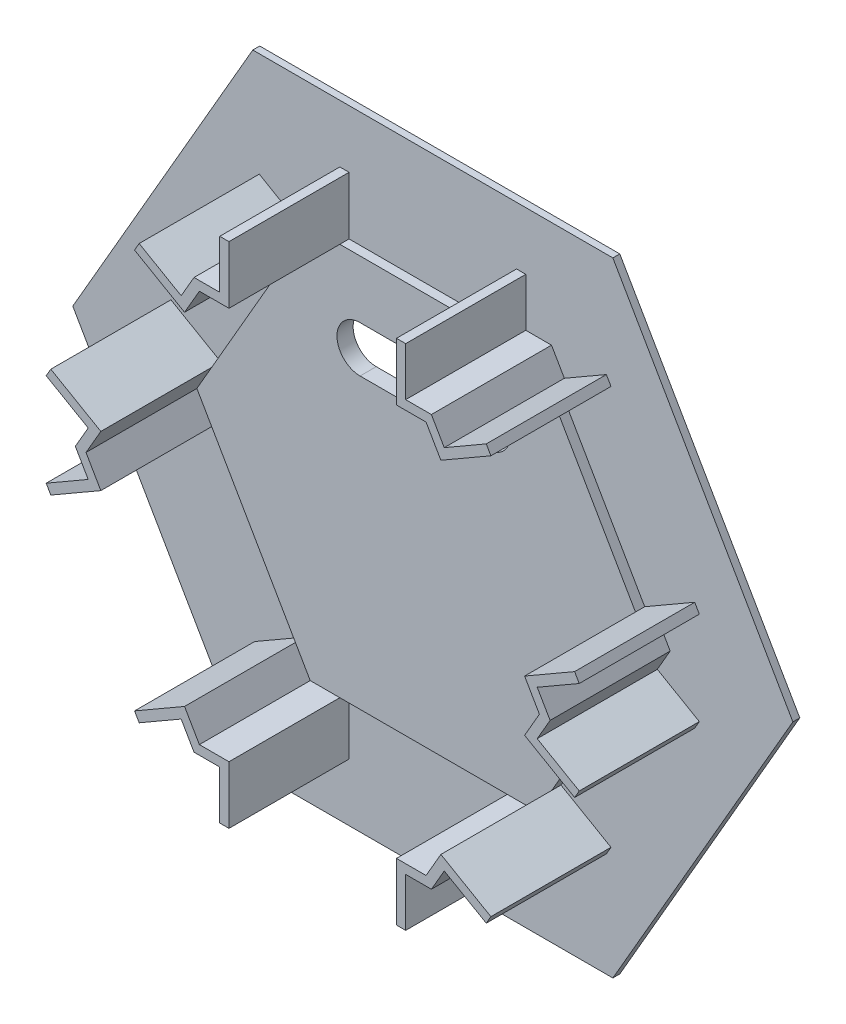
SolidWorks part; units mm, degrees
ref_plane "Спереди" through (0, 0, 0) normal (0, 0, 1) x (1, 0, 0)
ref_plane "Сверху" through (0, 0, 0) normal (0, 1, 0) x (1, 0, 0)
ref_plane "Справа" through (0, 0, 0) normal (1, 0, 0) x (0, 0, -1)
sketch "Sketch1" plane through (0, 0, 0) normal (0, 0, 1) x (1, 0, 0)
  line L2 (19.6299, 0) -> (9.815, 17)
  line L3 (9.815, 17) -> (-9.815, 17)
  line L4 (-9.815, 17) -> (-19.6299, 0)
  line L5 (-19.6299, 0) -> (-9.815, -17)
  line L6 (-9.815, -17) -> (9.815, -17)
  line L7 (9.815, -17) -> (19.6299, 0)
  circle A0 centre (0, 0) radius 17 construction
  point P0 (0, 0)
  dimension "D1" = 34
extrude "Boss-Extrude1" add sketch "Sketch1" along normal blind 1.4 contours L4 L5 L6 L7 L2 L3
sketch "Sketch2" plane through (0, 0, 0) normal (0, 0, 1) x (1, 0, 0)
  line L0 (9.815, 17) -> (-9.815, 17) construction
  line L1 (-7.25, 27) -> (7.25, 27)
  line L2 (-7.25, 27) -> (-7.25, 17)
  line L3 (-7.25, 17) -> (7.25, 17)
  line L4 (7.25, 27) -> (7.25, 17)
  line L5 (-7.25, 27) -> (7.25, 17) construction
  line L6 (-7.25, 17) -> (7.25, 27) construction
  line L7 (19.7577, 19.7787) -> (27.0077, 7.2213)
  line L8 (19.7577, 19.7787) -> (11.0974, 14.7787)
  line L9 (11.0974, 14.7787) -> (18.3474, 2.2213)
  line L10 (27.0077, 7.2213) -> (18.3474, 2.2213)
  line L11 (19.7577, 19.7787) -> (18.3474, 2.2213) construction
  line L12 (11.0974, 14.7787) -> (27.0077, 7.2213) construction
  line L13 (27.0077, -7.2213) -> (19.7577, -19.7787)
  line L14 (27.0077, -7.2213) -> (18.3474, -2.2213)
  line L15 (18.3474, -2.2213) -> (11.0974, -14.7787)
  line L16 (19.7577, -19.7787) -> (11.0974, -14.7787)
  line L17 (27.0077, -7.2213) -> (11.0974, -14.7787) construction
  line L18 (18.3474, -2.2213) -> (19.7577, -19.7787) construction
  line L19 (7.25, -27) -> (-7.25, -27)
  line L20 (7.25, -27) -> (7.25, -17)
  line L21 (7.25, -17) -> (-7.25, -17)
  line L22 (-7.25, -27) -> (-7.25, -17)
  line L23 (7.25, -27) -> (-7.25, -17) construction
  line L24 (7.25, -17) -> (-7.25, -27) construction
  line L25 (-19.7577, -19.7787) -> (-27.0077, -7.2213)
  line L26 (-19.7577, -19.7787) -> (-11.0974, -14.7787)
  line L27 (-11.0974, -14.7787) -> (-18.3474, -2.2213)
  line L28 (-27.0077, -7.2213) -> (-18.3474, -2.2213)
  line L29 (-19.7577, -19.7787) -> (-18.3474, -2.2213) construction
  line L30 (-11.0974, -14.7787) -> (-27.0077, -7.2213) construction
  line L31 (-27.0077, 7.2213) -> (-19.7577, 19.7787)
  line L32 (-27.0077, 7.2213) -> (-18.3474, 2.2213)
  line L33 (-18.3474, 2.2213) -> (-11.0974, 14.7787)
  line L34 (-19.7577, 19.7787) -> (-11.0974, 14.7787)
  line L35 (-27.0077, 7.2213) -> (-11.0974, 14.7787) construction
  line L36 (-18.3474, 2.2213) -> (-19.7577, 19.7787) construction
  point P0 (0, 22)
  point P6 (0, 0)
  point P8 (19.0526, 11)
  point P16 (19.0526, -11)
  point P21 (0, -22)
  point P26 (-19.0526, -11)
  point P31 (-19.0526, 11)
  point P42 (0, 0)
  point P43 (0, 0)
  dimension "D1" = 10
  dimension "D2" = 14.5
  dimension "D3" = 6
extrude "Boss-Extrude2" add sketch "Sketch2" along normal blind 0.6
sketch "Sketch3" plane through (0, 0, 0) normal (0, 0, 1) x (1, 0, 0)
  line L1 (-7.25, 22) -> (-8.05, 22)
  line L2 (-7.25, 27) -> (-7.25, 17) construction
  line L3 (-8.05, 22) -> (-8.05, 17.8)
  line L4 (-8.05, 17.8) -> (-10.2768, 17.8)
  line L5 (-10.2768, 17.8) -> (-11.3903, 15.8715)
  line L6 (-11.3903, 15.8715) -> (-15.0276, 17.9715)
  line L7 (-15.0276, 17.9715) -> (-15.4276, 17.2787)
  line L8 (-11.0974, 14.7787) -> (-19.7577, 19.7787) construction
  line L9 (-15.4276, 17.2787) -> (-11.0974, 14.7787)
  line L13 (-11.0974, 14.7787) -> (-9.815, 17)
  line L14 (-9.815, 17) -> (-7.25, 17)
  line L15 (-7.25, 17) -> (-7.25, 22)
  line L16 (15.4276, 17.2787) -> (15.0276, 17.9715)
  line L17 (15.0276, 17.9715) -> (11.3903, 15.8715)
  line L18 (11.3903, 15.8715) -> (10.2768, 17.8)
  line L19 (10.2768, 17.8) -> (8.05, 17.8)
  line L20 (8.05, 17.8) -> (8.05, 22)
  line L21 (8.05, 22) -> (7.25, 22)
  line L22 (7.25, 22) -> (7.25, 17)
  line L23 (7.25, 17) -> (9.815, 17)
  line L24 (9.815, 17) -> (11.0974, 14.7787)
  line L25 (11.0974, 14.7787) -> (15.4276, 17.2787)
  line L26 (22.6776, -4.7213) -> (23.0776, -4.0285)
  line L27 (23.0776, -4.0285) -> (19.4403, -1.9285)
  line L28 (19.4403, -1.9285) -> (20.5537, 0)
  line L29 (20.5537, 0) -> (19.4403, 1.9285)
  line L30 (19.4403, 1.9285) -> (23.0776, 4.0285)
  line L31 (23.0776, 4.0285) -> (22.6776, 4.7213)
  line L32 (22.6776, 4.7213) -> (18.3474, 2.2213)
  line L33 (18.3474, 2.2213) -> (19.6299, 0)
  line L34 (19.6299, 0) -> (18.3474, -2.2213)
  line L35 (18.3474, -2.2213) -> (22.6776, -4.7213)
  line L36 (7.25, -22) -> (8.05, -22)
  line L37 (8.05, -22) -> (8.05, -17.8)
  line L38 (8.05, -17.8) -> (10.2768, -17.8)
  line L39 (10.2768, -17.8) -> (11.3903, -15.8715)
  line L40 (11.3903, -15.8715) -> (15.0276, -17.9715)
  line L41 (15.0276, -17.9715) -> (15.4276, -17.2787)
  line L42 (15.4276, -17.2787) -> (11.0974, -14.7787)
  line L43 (11.0974, -14.7787) -> (9.815, -17)
  line L44 (9.815, -17) -> (7.25, -17)
  line L45 (7.25, -17) -> (7.25, -22)
  line L46 (-15.4276, -17.2787) -> (-15.0276, -17.9715)
  line L47 (-15.0276, -17.9715) -> (-11.3903, -15.8715)
  line L48 (-11.3903, -15.8715) -> (-10.2768, -17.8)
  line L49 (-10.2768, -17.8) -> (-8.05, -17.8)
  line L50 (-8.05, -17.8) -> (-8.05, -22)
  line L51 (-8.05, -22) -> (-7.25, -22)
  line L52 (-7.25, -22) -> (-7.25, -17)
  line L53 (-7.25, -17) -> (-9.815, -17)
  line L54 (-9.815, -17) -> (-11.0974, -14.7787)
  line L55 (-11.0974, -14.7787) -> (-15.4276, -17.2787)
  line L56 (-22.6776, 4.7213) -> (-23.0776, 4.0285)
  line L57 (-23.0776, 4.0285) -> (-19.4403, 1.9285)
  line L58 (-19.4403, 1.9285) -> (-20.5537, 0)
  line L59 (-20.5537, 0) -> (-19.4403, -1.9285)
  line L60 (-19.4403, -1.9285) -> (-23.0776, -4.0285)
  line L61 (-23.0776, -4.0285) -> (-22.6776, -4.7213)
  line L62 (-22.6776, -4.7213) -> (-18.3474, -2.2213)
  line L63 (-18.3474, -2.2213) -> (-19.6299, 0)
  line L64 (-19.6299, 0) -> (-18.3474, 2.2213)
  line L65 (-18.3474, 2.2213) -> (-22.6776, 4.7213)
  point P4 (-8.5325, 17)
  point P16 (0, 0)
  point P69 (0, 0)
  dimension "D1" = 0.8
  dimension "D2" = 5
  dimension "D3" = 0.8
extrude "Boss-Extrude3" add sketch "Sketch3" along normal blind 11
sketch "Sketch4" plane through (0, 0, 0) normal (0, 0, 1) x (1, 0, 0)
  line L1 (31.1769, 0) -> (15.5885, 27)
  line L2 (15.5885, 27) -> (-15.5885, 27)
  line L3 (-15.5885, 27) -> (-31.1769, 0)
  line L4 (-31.1769, 0) -> (-15.5885, -27)
  line L5 (-15.5885, -27) -> (15.5885, -27)
  line L6 (15.5885, -27) -> (31.1769, 0)
  circle A0 centre (0, 0) radius 27 construction
  point P1 (0, 0)
  dimension "D1" = 54
extrude "Boss-Extrude4" add sketch "Sketch4" along normal blind 0.6
sketch "Sketch5" plane through (0, 0, 1.4) normal (0, 0, 1) x (1, 0, 0)
  line L0 (-5.5, 10) -> (5.5, 10) construction
  line L1 (-5.5, 12) -> (5.5, 12)
  line L2 (-5.5, 8) -> (5.5, 8)
  arc A0 (-5.5, 12) -> (-5.5, 8) centre (-5.5, 10) ccw
  arc A1 (5.5, 8) -> (5.5, 12) centre (5.5, 10) ccw
  point P2 (0, 0)
  point P3 (0, 10)
  point P8 (0, 0)
  point P10 (0, 8)
  dimension "D1" = 4
  dimension "D2" = 11
  dimension "D3" = 8
extrude "Cut-Extrude1" cut sketch "Sketch5" against normal through all both and the other way through all
